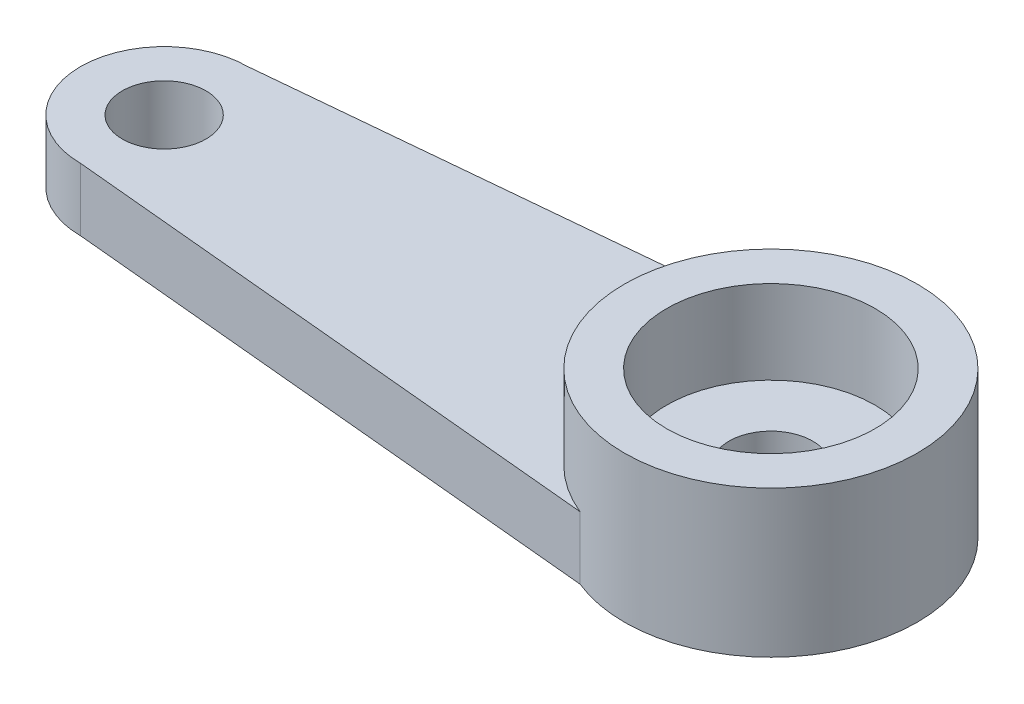
SolidWorks part; units mm, degrees
ref_plane "前视基准面" through (0, 0, 0) normal (0, 0, 1) x (1, 0, 0)
ref_plane "上视基准面" through (0, 0, 0) normal (0, 1, 0) x (1, 0, 0)
ref_plane "右视基准面" through (0, 0, 0) normal (1, 0, 0) x (0, 0, -1)
sketch "草图1" plane through (0, 0, 0) normal (0, 1, 0) x (1, 0, 0)
  line L0 (-14.5, 2) -> (-1.3197, 3.2417)
  line L1 (-14.5, -2) -> (-1.3197, -3.2417)
  arc A0 (-1.3197, -3.2417) -> (-1.3197, 3.2417) centre (0, 0) ccw
  circle A1 centre (-14.5, 0) radius 1
  arc A2 (-14.5, 2) -> (-14.5, -2) centre (-14.5, 0) ccw
  circle A3 centre (0, 0) radius 1
  dimension "D1" = 14.5
  dimension "D2" = 2
  dimension "D3" = 3.5
extrude "凸台-拉伸1" add sketch "草图1" along normal blind 1.5
sketch "草图3" plane through (0, 1.5, 0) normal (0, 1, 0) x (1, 0, 0)
  circle A0 centre (0, 0) radius 3.5
  circle A1 centre (0, 0) radius 2.4904
extrude "凸台-拉伸2" add sketch "草图3" along normal blind 2
